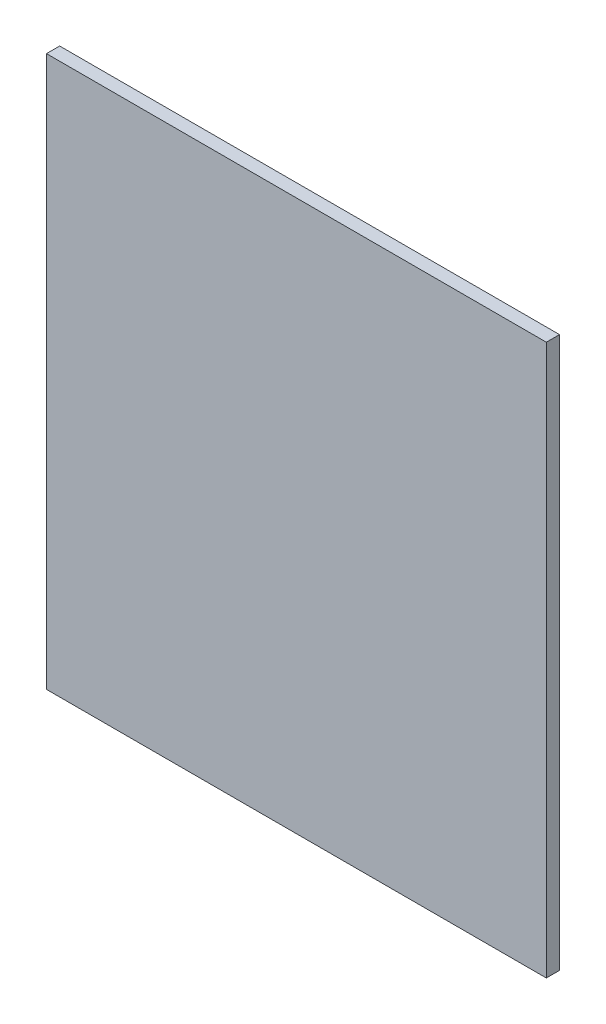
SolidWorks part; units mm, degrees
ref_plane "Спереди" through (0, 0, 0) normal (0, 0, 1) x (1, 0, 0)
ref_plane "Сверху" through (0, 0, 0) normal (0, 1, 0) x (1, 0, 0)
ref_plane "Справа" through (0, 0, 0) normal (1, 0, 0) x (0, 0, -1)
sketch "Эскиз1" plane through (0, 0, 0) normal (0, 0, 1) x (1, 0, 0)
  line L1 (0, 0) -> (75.8, 0)
  line L2 (0, 0) -> (0, 83.5)
  line L3 (0, 83.5) -> (75.8, 83.5)
  line L4 (75.8, 0) -> (75.8, 83.5)
  dimension "D1" = 83.5
  dimension "D2" = 75.8
extrude "Бобышка-Вытянуть1" add sketch "Эскиз1" along normal blind 2
